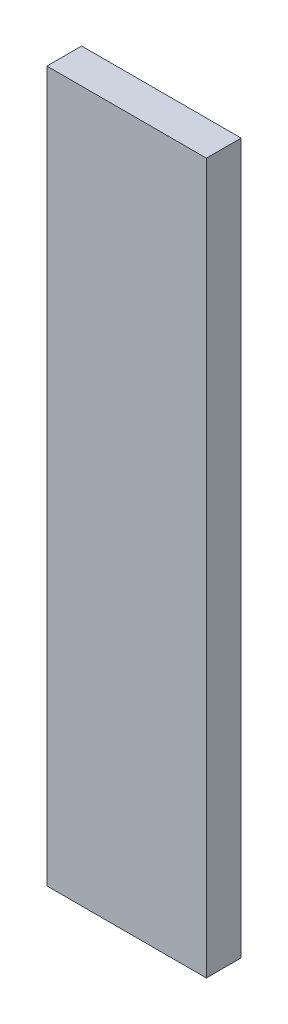
SolidWorks part; units mm, degrees
ref_plane "Front Plane" through (0, 0, 0) normal (0, 0, 1) x (1, 0, 0)
ref_plane "Top Plane" through (0, 0, 0) normal (0, 1, 0) x (1, 0, 0)
ref_plane "Right Plane" through (0, 0, 0) normal (1, 0, 0) x (0, 0, -1)
sketch "Sketch1" plane through (0, 0, 0) normal (0, 0, 1) x (1, 0, 0)
  line L1 (-21.7182, 31.0897) -> (10.4018, 31.0897)
  line L2 (-21.7182, 31.0897) -> (-21.7182, -111.9103)
  line L3 (-21.7182, -111.9103) -> (10.4018, -111.9103)
  line L4 (10.4018, 31.0897) -> (10.4018, -111.9103)
  dimension "D1" = 32.12
  dimension "D2" = 143
extrude "Boss-Extrude1" add sketch "Sketch1" along normal blind 7
